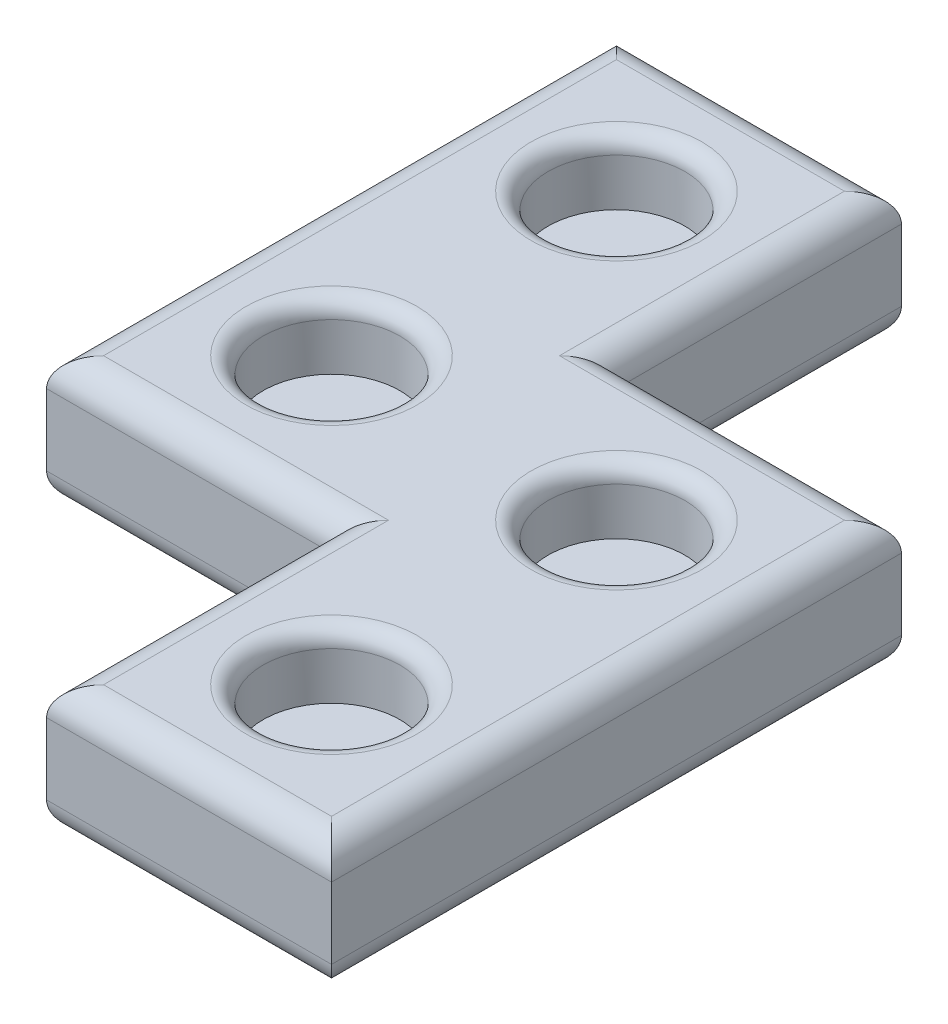
SolidWorks part; units mm, degrees
ref_plane "Front Plane" through (0, 0, 0) normal (0, 0, 1) x (1, 0, 0)
ref_plane "Top Plane" through (0, 0, 0) normal (0, 1, 0) x (1, 0, 0)
ref_plane "Right Plane" through (0, 0, 0) normal (1, 0, 0) x (0, 0, -1)
sketch "Sketch1" plane through (0, 0, 0) normal (0, 1, 0) x (1, 0, 0)
  line L0 (-12.7, 15.597) -> (0, 15.597)
  line L1 (0, 15.597) -> (0, 2.897)
  line L2 (0, 2.897) -> (12.7, 2.897)
  line L3 (12.7, 2.897) -> (12.7, -22.503)
  line L4 (12.7, -22.503) -> (0, -22.503)
  line L5 (0, -22.503) -> (0, -9.803)
  line L6 (0, -9.803) -> (-12.7, -9.803)
  line L7 (-12.7, -9.803) -> (-12.7, 15.597)
  dimension "D1" = 12.7
  dimension "D2" = 25.4
  dimension "D3" = 12.7
  dimension "D4" = 12.7
  dimension "D5" = 25.4
extrude "Boss-Extrude2" add sketch "Sketch1" along normal blind 5.715 contours L7 L0 L1 L2 L3 L4 L5 L6
sketch "Sketch2" plane through (0, 5.715, 0) normal (0, 1, 0) x (1, 0, 0)
  line L0 (0, 15.597) -> (0, 2.897) construction
  line L1 (12.7, -22.503) -> (0, -22.503) construction
  circle A0 centre (-6.35, 9.247) radius 3.048
  circle A1 centre (6.35, -16.153) radius 3.048
  circle A2 centre (-6.35, -3.453) radius 3.048
  circle A3 centre (6.35, -3.453) radius 3.048
  dimension "D1" = 6.35
  dimension "D2" = 12.7
  dimension "D3" = 12.7
  dimension "D4" = 6.35
  dimension "D5" = 12.7
extrude "Cut-Extrude1" cut sketch "Sketch2" against normal blind 2.8702
sketch "Sketch3" plane through (0, 0, 0) normal (0, 1, 0) x (1, 0, 0)
  line L0 (-24.8243, 25.5073) -> (-24.8243, -34.1491) construction
ref_plane "Plane1" through (-24.8243, 0, 0) normal (-1, 0, 0) x (0, 0, 1)
fillet "Fillet1" radius 1.27 8 edges at (-12.7, 5.715, -2.897) (-6.35, 5.715, 9.803) (0, 5.715, 16.153) (6.35, 5.715, 22.503) (12.7, 5.715, 9.803) (6.35, 5.715, -2.897) (0, 5.715, -9.247) (-6.35, 5.715, -15.597)
fillet "Fillet2" radius 1.27 8 edges at (6.35, 0, -2.897) (0, 0, -9.247) (-6.35, 0, -15.597) (-12.7, 0, -2.897) (-6.35, 0, 9.803) (0, 0, 16.153) (6.35, 0, 22.503) (12.7, 0, 9.803)
fillet "Fillet3" radius 0.762 4 edges at (6.35, 5.715, 19.201) (6.35, 5.715, 6.501) (-6.35, 5.715, 6.501) (-6.35, 5.715, -6.199)
